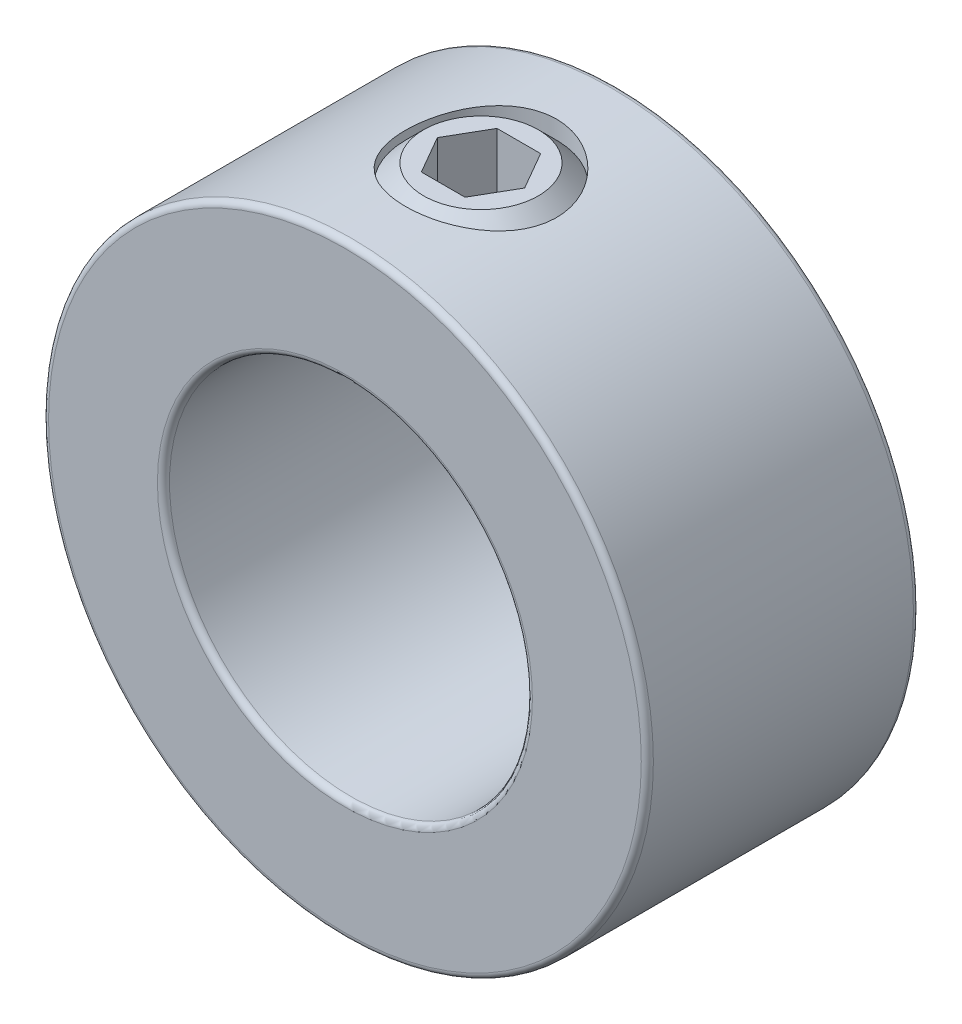
SolidWorks part; units mm, degrees
ref_plane "Front Plane" through (0, 0, 0) normal (0, 0, 1) x (1, 0, 0)
ref_plane "Top Plane" through (0, 0, 0) normal (0, 1, 0) x (1, 0, 0)
ref_plane "Right Plane" through (0, 0, 0) normal (1, 0, 0) x (0, 0, -1)
sketch "Sketch1" plane through (0, 0, 0) normal (0, 0, 1) x (1, 0, 0)
  circle A0 centre (0, 0) radius 15.875
  circle A1 centre (0, 0) radius 9.525
  point P4 (15.875, 0)
  dimension "Bore Dia" = 19.05
  dimension "OD" = 31.75
extrude "Extrude1" add sketch "Sketch1" along normal mid plane 14.2875
sketch "Sketch2" plane through (41.275, 0, 0) normal (0, -1, 0) x (0, 0, -1)
  line L0 (7.1437, -41.275) -> (-7.1438, -41.275) construction
  line L1 (-7.1437, -25.4) -> (-7.1437, -57.15) construction
  line L2 (7.1437, -57.15) -> (7.1437, -25.4) construction
  circle A0 centre (0, -41.275) radius 3.9688
  point P7 (0, -45.2437)
  dimension "Set Screw Dia" = 7.9375
extrude "Cut-Extrude1" cut sketch "Sketch2" against normal through all
fillet "Fillet1" radius 0.3175 4 edges at (9.525, 0, -7.1437) (9.525, 0, 7.1437) (15.875, 0, -7.1437) (15.875, 0, 7.1437)
sketch "Sketch3" plane through (0, 0, 0) normal (0, 0, 1) x (1, 0, 0)
  line L0 (-3.0102, 9.525) -> (-1.1502, 9.525)
  line L1 (0, 10.6752) -> (-1.1502, 9.525)
  line L2 (0, 10.6752) -> (0, 15.875)
  line L3 (0, 15.875) -> (-3.0102, 15.875)
  line L4 (-3.9688, 10.4835) -> (-3.9688, 14.9165)
  line L5 (0, 9.525) -> (0, 0) construction
  line L6 (-3.9688, 10.4835) -> (-3.9688, 9.525) construction
  line L7 (-3.9688, 9.525) -> (-3.0102, 9.525) construction
  line L8 (-3.9688, 14.9165) -> (-3.9688, 15.875) construction
  line L9 (-3.0102, 9.525) -> (-3.9688, 10.4835)
  line L10 (-3.9688, 14.9165) -> (-3.0102, 15.875)
  line L11 (-3.9688, 15.875) -> (-3.0102, 15.875) construction
  line L12 (-1.1502, 9.525) -> (0, 9.525) construction
  line L13 (0, 9.525) -> (0, 10.6752) construction
  circle A1 centre (0, 0) radius 9.525 construction
  dimension "D1" = 1.1502
  dimension "D2" = 0.9585
  dimension "Screw Length" = 6.35
revolve "Revolve1" add sketch "Sketch3" angle 360 about L5
sketch "Sketch4" plane through (3.3734, 15.875, 0) normal (0, -1, 0) x (0, 0, -1)
  line L1 (0, -1.0821) -> (-1.9844, -2.2278)
  line L2 (-1.9844, -2.2278) -> (-1.9844, -4.5191)
  line L3 (-1.9844, -4.5191) -> (0, -5.6648)
  line L4 (0, -5.6648) -> (1.9844, -4.5191)
  line L5 (1.9844, -4.5191) -> (1.9844, -2.2278)
  line L6 (1.9844, -2.2278) -> (0, -1.0821)
  circle A0 centre (0, -3.3734) radius 1.9844 construction
  circle A1 centre (0, -3.3734) radius 2.2914 construction
  dimension "D1" = 4.5827
  dimension "Hex Size" = 3.9688
extrude "Cut-Extrude2" cut sketch "Sketch4" along normal blind 3.9688
equation "\"D1@Fillet1\" = \"OD@Sketch1\"*.01"
equation "\"D1@Cut-Extrude2\" = \"Hex Size@Sketch4\""
equation "\"D2@Sketch3\" =(\"Set Screw Dia@Sketch2\"-\"D1@Sketch4\")/3.5"
equation "\"D1@Sketch3\" = \"D2@Sketch3\"*1.2"
